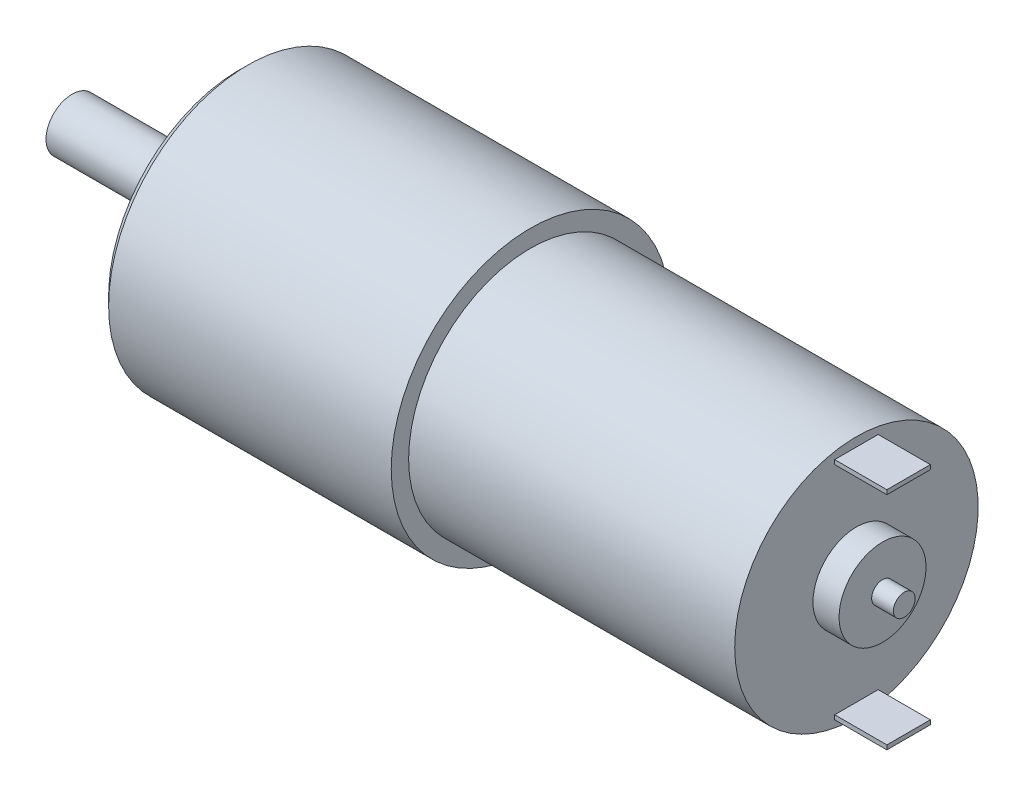
SolidWorks part; units mm, degrees
material "0.6010 (EN-GJL-100)"
ref_plane "正面" through (0, 0, 0) normal (0, 0, 1) x (1, 0, 0)
ref_plane "平面" through (0, 0, 0) normal (0, 1, 0) x (1, 0, 0)
ref_plane "右側面" through (0, 0, 0) normal (1, 0, 0) x (0, 0, -1)
sketch "ｽｹｯﾁ1" plane through (0, 0, 0) normal (0, 1, 0) x (1, 0, 0)
  line L0 (0, 0) -> (0, 3)
  line L1 (0, 3) -> (15, 3)
  line L2 (15, 3) -> (15, 5.5)
  line L3 (15, 5.5) -> (15.8, 5.5)
  line L4 (15.8, 5.5) -> (15.8, 7)
  line L5 (16.2, 7) -> (15.8, 7)
  line L6 (16.2, 7) -> (16.2, 10)
  line L7 (16.2, 10) -> (19.2, 10)
  line L8 (19.2, 10) -> (19.2, 16)
  line L9 (19.2, 16) -> (52.7, 16)
  line L10 (52.7, 16) -> (52.7, 14)
  line L11 (52.7, 14) -> (90.2, 14)
  line L12 (90.2, 14) -> (90.2, 5)
  line L13 (90.2, 5) -> (93.2, 5)
  line L14 (93.2, 5) -> (93.2, 1.25)
  line L15 (93.2, 1.25) -> (95.7, 1.25)
  line L16 (95.7, 1.25) -> (95.7, 0)
  line L17 (0, 0) -> (95.7, 0) construction
  line L18 (0, 0) -> (95.7, 0)
  dimension "D1" = 3
  dimension "D2" = 15
  dimension "D3" = 5.5
  dimension "D4" = 0.8
  dimension "D5" = 7
  dimension "D6" = 0.4
  dimension "D7" = 10
  dimension "D8" = 3
  dimension "D9" = 16
  dimension "D10" = 33.5
  dimension "D11" = 2
  dimension "D12" = 37.5
  dimension "D13" = 9
  dimension "D14" = 1.25
  dimension "D15" = 2.5
revolve "回転2" add sketch "ｽｹｯﾁ1" angle 360 about L17
sketch "ｽｹｯﾁ2" plane through (16.2, 0, 0) normal (-1, 0, 0) x (0, 0, 1)
  line L1 (-10, -9) -> (10, -9)
  line L2 (-10, -9) -> (-10, 9)
  line L3 (-10, 9) -> (10, 9)
  line L4 (10, -9) -> (10, 9)
  line L5 (-10, -9) -> (10, 9) construction
  line L6 (-10, 9) -> (10, -9) construction
  point P0 (0, 0)
  dimension "D1" = 18
  dimension "D2" = 20
extrude "ｶｯﾄ - 押し出し1" cut sketch "ｽｹｯﾁ2" against normal blind 3 flip side to cut
sketch "ｽｹｯﾁ3" plane through (19.2, 0, 0) normal (-1, 0, 0) x (0, 0, 1)
  circle A0 centre (0, 0) radius 13
  arc A5 (0, -13) -> (-9.1924, -9.1924) centre (0, 0) cw
  circle A6 centre (-9.1924, -9.1924) radius 1.5
  dimension "D1" = 3
chamfer "面取り1" distance 1 angle 45 1 edges at (19.2, 0, 16)
sketch "ｽｹｯﾁ4" plane through (90.2, 0, 0) normal (1, 0, 0) x (0, 0, -1)
  line L0 (0, 0) -> (0, 12.957) construction
  line L1 (0, 12.957) -> (0, -12.4399) construction
  line L2 (0, 12.957) -> (2.5, 12.957)
  line L3 (-2.5, 12.957) -> (0, 12.957)
  line L4 (2.5, 12.957) -> (2.5, 12.457)
  line L5 (-2.5, 12.457) -> (-2.5, 12.957)
  line L6 (-2.5, 12.457) -> (2.5, 12.457)
  dimension "D1" = 2.5
  dimension "D2" = 2.5
  dimension "D3" = 0.5
extrude "ｶｯﾄ - 押し出し3" cut sketch "ｽｹｯﾁ3" against normal blind 3 contours A6
pattern_circular "円形ﾊﾟﾀｰﾝ2" count 4 over 360 about axis through (0, 0, 0) along (1, 0, 0) of "ｶｯﾄ - 押し出し3"
sketch "ｽｹｯﾁ5" plane through (19.2, 0, 0) normal (-1, 0, 0) x (0, 0, 1)
extrude "ﾎﾞｽ - 押し出し2" add sketch "ｽｹｯﾁ4" along normal blind 6
pattern_circular "円形ﾊﾟﾀｰﾝ3" count 2 over 360 about axis through (0, 0, 0) along (1, 0, 0) of "ﾎﾞｽ - 押し出し2"
